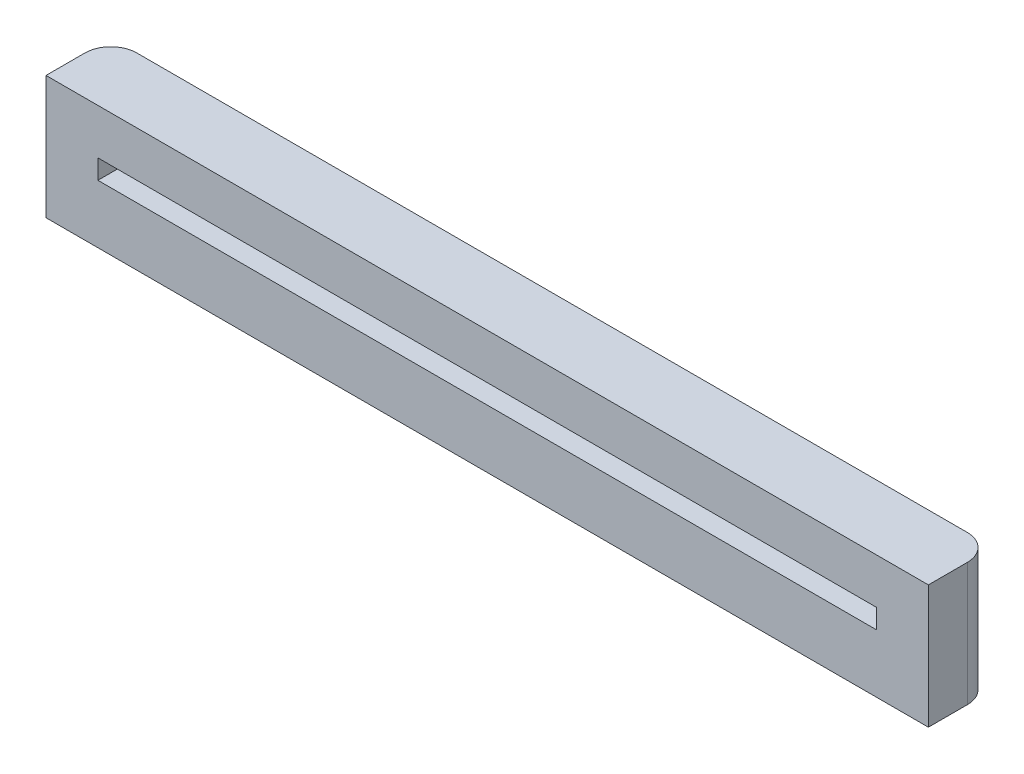
SolidWorks part; units mm, degrees
ref_plane "Front Plane" through (0, 0, 0) normal (0, 0, 1) x (1, 0, 0)
ref_plane "Top Plane" through (0, 0, 0) normal (0, 1, 0) x (1, 0, 0)
ref_plane "Right Plane" through (0, 0, 0) normal (1, 0, 0) x (0, 0, -1)
sketch "Sketch1" plane through (0, 0, 0) normal (0, 0, 1) x (1, 0, 0)
  line L1 (0, 0) -> (68, 0)
  line L2 (0, 0) -> (0, 9.5)
  line L3 (0, 9.5) -> (68, 9.5)
  line L4 (68, 0) -> (68, 9.5)
  dimension "D1" = 68
  dimension "D2" = 9.5
extrude "Boss-Extrude1" add sketch "Sketch1" along normal blind 5
sketch "Sketch2" plane through (0, 0, 5) normal (0, 0, 1) x (1, 0, 0)
  line L0 (68, 9.5) -> (0, 9.5) construction
  line L1 (4, 6) -> (64, 6)
  line L2 (4, 6) -> (4, 4.5)
  line L3 (4, 4.5) -> (64, 4.5)
  line L4 (64, 6) -> (64, 4.5)
  line L5 (0, 9.5) -> (0, 0) construction
  dimension "D1" = 60
  dimension "D2" = 1.5
  dimension "D3" = 3.5
  dimension "D4" = 4
extrude "Cut-Extrude1" cut sketch "Sketch2" against normal blind 3
fillet "Fillet1" radius 2 2 edges at (68, 4.75, 0) (0, 4.75, 0)
